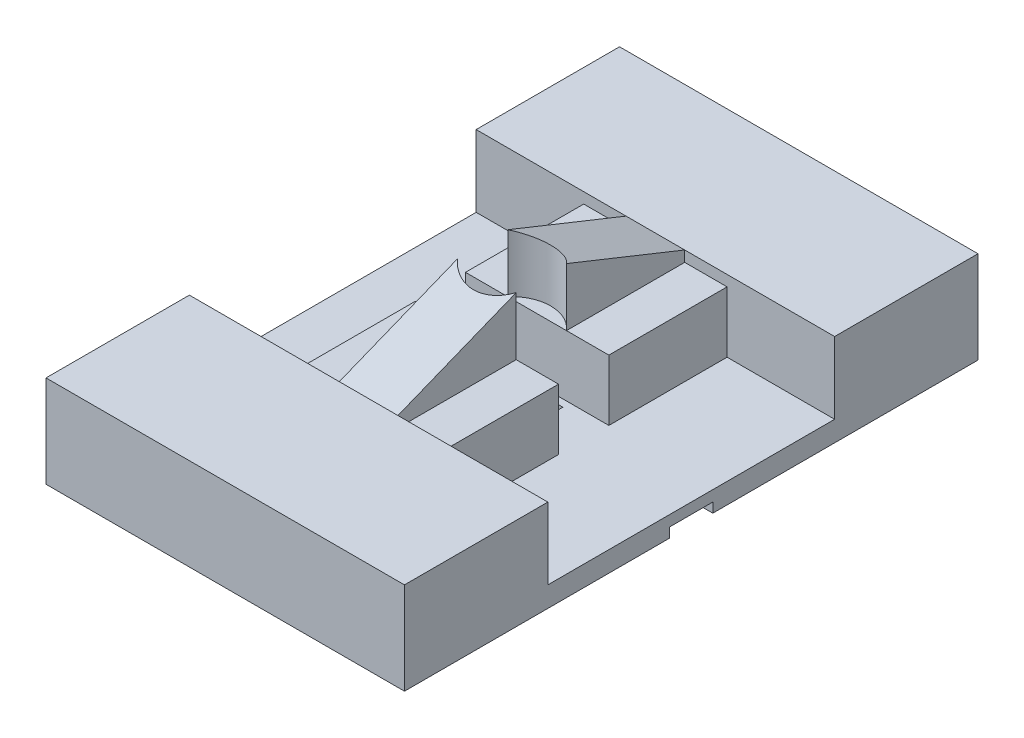
SolidWorks part; units mm, degrees
ref_plane "Front Plane" through (0, 0, 0) normal (0, 0, 1) x (1, 0, 0)
ref_plane "Top Plane" through (0, 0, 0) normal (0, 1, 0) x (1, 0, 0)
ref_plane "Right Plane" through (0, 0, 0) normal (1, 0, 0) x (0, 0, -1)
sketch "Sketch1" plane through (0, 0, 0) normal (0, 1, 0) x (1, 0, 0)
  line L0 (-2, -2) -> (10.18, -2)
  line L5 (10.18, -2) -> (10.18, 0)
  line L6 (10.18, 6.02) -> (10.18, 0)
  line L7 (10.18, 6.02) -> (10.18, 8.02)
  line L8 (10.18, 8.02) -> (-2, 8.02)
  line L9 (-2, 8.02) -> (-2, -2)
  line L10 (8.68, 6.02) -> (10.18, 6.02)
  line L11 (8.68, 0) -> (10.18, 0)
  line L36 (8.68, 6.02) -> (8.68, 0)
  line L41 (8.68, -0.5) -> (8.68, 0)
  line L42 (8.68, 6.02) -> (8.68, 6.52)
  line L43 (8.68, 6.52) -> (-0.5, 6.52)
  line L44 (-0.5, 6.52) -> (-0.5, -0.5)
  line L45 (-0.5, -0.5) -> (8.68, -0.5)
  dimension "D2" = 0.5
  dimension "D3" = 0.5
  dimension "D1" = 1.5
extrude "Boss-Extrude1" add sketch "Sketch1" along normal offset from surface (3.15 mm away) 1.5 contours L45 L44 L43 L42 L10 L7 L8 L9 L0 L5 L11 L41
sketch "Sketch3" plane through (0, 3.15, 0) normal (0, 1, 0) x (1, 0, 0)
  line L30 (8.68, 0.5) -> (8.68, 5.52)
  line L31 (-2, 8.02) -> (-2, -2) construction
  line L32 (-2, -2) -> (10.18, -2)
  line L33 (8.68, 5.52) -> (0.5, 5.52)
  line L34 (0.5, 5.52) -> (0.5, 0.5)
  line L35 (0.5, 0.5) -> (8.68, 0.5)
  line L36 (8.68, 5.52) -> (0.5, 5.52)
  line L37 (0.5, 5.52) -> (0.5, 0.5)
  line L38 (0.5, 0.5) -> (8.68, 0.5)
  line L39 (-2, -2) -> (-2, 8.02)
  line L40 (-2, 8.02) -> (10.18, 8.02)
  line L41 (10.18, -2) -> (10.18, 8.02)
  line L42 (10.18, 6.02) -> (10.18, 8.02) construction
  dimension "D1" = 1
extrude "Boss-Extrude2" add sketch "Sketch3" against normal blind 1.5
sketch "Sketch5" plane through (0, 0, 0) normal (0, -1, 0) x (1, 0, 0)
  line L0 (10.18, -6.02) -> (10.18, -8.02) construction
  line L1 (10.18, -8.02) -> (-2, -8.02)
  line L2 (10.18, -8.02) -> (10.18, 2)
  line L3 (10.18, 2) -> (-2, 2)
  line L4 (-2, -8.02) -> (-2, 2)
  line L5 (10.18, -8.02) -> (-2, -8.02) construction
  line L6 (-2, -8.02) -> (-2, 2) construction
extrude "Cut-Extrude1" cut sketch "Sketch5" against normal blind 0.3
sketch "Sketch7" plane through (0, 3.15, 0) normal (0, 1, 0) x (1, 0, 0)
  line L10 (-2, 3.01) -> (10.18, 3.01) construction
  line L11 (-20.91, -36.99) -> (29.09, -36.99)
  line L12 (-20.91, -36.99) -> (-20.91, 43.01)
  line L13 (-20.91, 43.01) -> (29.09, 43.01)
  line L14 (-2, 8.02) -> (-2, -2)
  line L15 (10.18, 8.02) -> (-2, 8.02)
  line L16 (10.18, -2) -> (10.18, 8.02)
  line L17 (-2, -2) -> (10.18, -2)
  line L18 (-2, 8.02) -> (-2, -2)
  line L19 (10.18, 8.02) -> (-2, 8.02)
  line L20 (10.18, -2) -> (10.18, 8.02)
  line L21 (-2, -2) -> (10.18, -2)
  line L22 (29.09, -36.99) -> (29.09, 43.01)
  line L23 (4.09, 8.02) -> (4.09, -2) construction
  dimension "D2" = 80
  dimension "D3" = 40
  dimension "D4" = 50
  dimension "D5" = 25
  dimension "D1" = 0
extrude "Boss-Extrude7" add sketch "Sketch7" against normal up to surface (2.85 mm away) up to face at (5.87, 0.3, -3.01)
sketch "Sketch8" plane through (0, 3.15, 0) normal (0, 1, 0) x (1, 0, 0)
  line L0 (29.09, -36.99) -> (29.09, 43.01) construction
  line L1 (29.09, -36.99) -> (-20.91, -36.99)
  line L2 (29.09, -36.99) -> (29.09, -16.99)
  line L3 (29.09, -16.99) -> (-20.91, -16.99)
  line L4 (-20.91, -36.99) -> (-20.91, -16.99)
  line L5 (-20.91, -36.99) -> (29.09, -36.99) construction
  line L6 (-20.91, 43.01) -> (-20.91, -36.99) construction
  dimension "D1" = 20
extrude "Boss-Extrude8" add sketch "Sketch8" along normal blind 10
sketch "Sketch9" plane through (0, 0.3, 0) normal (0, -1, 0) x (1, 0, 0)
  line L0 (10.18, 0) -> (10.18, -6.02)
  line L1 (10.18, 0) -> (29.09, 0)
  line L2 (10.18, -6.02) -> (29.09, -6.02)
  line L3 (29.09, 0) -> (29.09, -6.02)
  line L4 (10.18, 0) -> (10.18, -6.02) construction
  line L5 (10.18, -6.02) -> (8.68, -6.02) construction
  line L7 (29.09, 36.99) -> (29.09, -43.01) construction
extrude "Cut-Extrude2" cut sketch "Sketch9" against normal up to surface (1.35 mm away) up to face at (4.59, 1.65, -3.01)
sketch "Sketch11" plane through (0, 3.15, 0) normal (0, 1, 0) x (1, 0, 0)
  line L0 (14.09, -0.5) -> (-5.91, -0.5)
  line L1 (14.09, -0.5) -> (14.09, -16.99)
  line L2 (-5.91, -0.5) -> (-5.91, -16.99)
  line L3 (14.09, -16.99) -> (-5.91, -16.99)
  line L6 (29.09, -16.99) -> (29.09, 43.01) construction
  line L8 (0.5, 0.5) -> (8.68, 0.5) construction
  line L9 (29.09, -16.99) -> (-20.91, -16.99) construction
  dimension "D1" = 20
  dimension "D2" = 15
  dimension "D3" = 1
extrude "Boss-Extrude9" add sketch "Sketch11" along normal up to surface (8.5 mm away)
sketch "Sketch12" plane through (0, 11.65, 0) normal (0, 1, 0) x (1, 0, 0)
  line L0 (-5.91, -0.5) -> (14.09, -0.5) construction
  line L1 (0, -0.5) -> (0, -16.99)
  line L2 (8.18, -0.5) -> (8.18, -16.99)
  line L3 (0, -16.99) -> (8.18, -16.99)
  arc A0 (0, -0.5) -> (8.18, -0.5) centre (4.09, 3.01) ccw
extrude "Boss-Extrude10" add sketch "Sketch12" along normal up to surface (8.1 mm away)
sketch "Sketch13" plane through (8.18, 0, 0) normal (1, 0, 0) x (0, 0, -1)
  line L0 (-16.99, 13.15) -> (-0.5, 19.75)
  line L1 (-16.99, 13.15) -> (-16.99, 11.65) construction
  line L2 (-16.99, 19.75) -> (-16.99, 13.15) construction
  line L3 (-0.5, 19.75) -> (-0.5, 11.65) construction
  line L4 (-0.5, 19.75) -> (-16.99, 19.75)
  line L5 (-16.99, 19.75) -> (-16.99, 13.15)
extrude "Cut-Extrude3" cut sketch "Sketch13" against normal blind 10
ref_plane "Plane2" through (0, 0, -3.01) normal (0, 0, 1) x (1, 0, 0)
mirror "Mirror2" about plane through (0, 0, -3.01) normal (0, 0, 1) of "Boss-Extrude8", "Boss-Extrude9", "Boss-Extrude10", "Cut-Extrude3"
